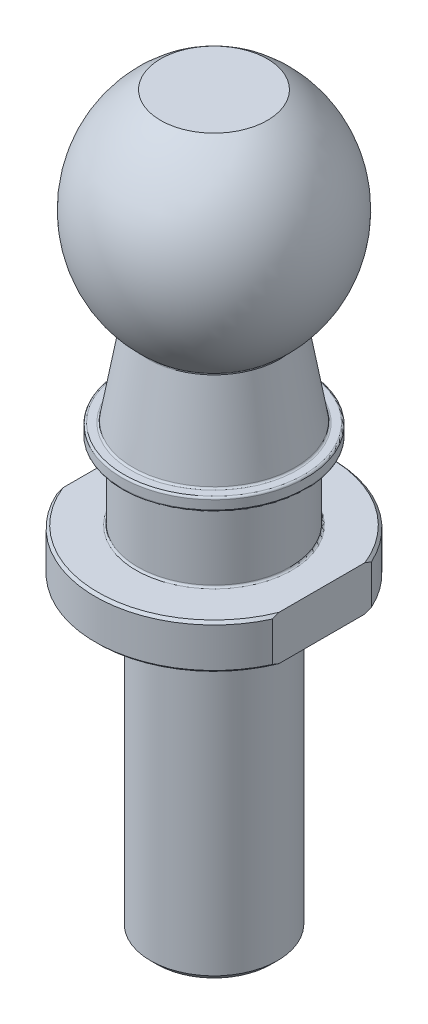
SolidWorks part; units mm, degrees
ref_plane "Plano frontal" through (0, 0, 0) normal (0, 0, 1) x (1, 0, 0)
ref_plane "Plano superior" through (0, 0, 0) normal (0, 1, 0) x (1, 0, 0)
ref_plane "Plano direito" through (0, 0, 0) normal (1, 0, 0) x (0, 0, -1)
sketch "Esboço1" plane through (0, 0, 0) normal (0, 0, 1) x (1, 0, 0)
  line L0 (0, 52.4807) -> (0, -52.9589) construction
  line L1 (0, -52.9589) -> (5, -52.9589)
  line L2 (5, -52.9589) -> (5, -28.7589)
  line L3 (5, -28.7589) -> (9.35, -28.7589)
  line L4 (9.35, -28.7589) -> (9.35, -25.2589)
  line L5 (9.35, -25.2589) -> (6, -25.2589)
  line L6 (6, -25.2589) -> (6, -19.2589)
  line L7 (6, -19.2589) -> (7.25, -19.2589)
  line L8 (7.25, -19.2589) -> (7.25, -18.2589)
  line L9 (7.25, -18.2589) -> (6.4, -18.2589)
  line L10 (6.4, -18.2589) -> (5.175, -11.2589)
  line L11 (4.2023, 4.4411) -> (0, 4.4411)
  line L12 (0, 4.4411) -> (0, -52.9589)
  arc A0 (5.175, -11.2589) -> (4.2023, 4.4411) centre (-0.9606, -3.7589) ccw
  dimension "D7" = 9.69
  dimension "D1" = 5
  dimension "D2" = 9.35
  dimension "D3" = 6
  dimension "D4" = 7.25
  dimension "D5" = 6.4
  dimension "D6" = 5.175
  dimension "D8" = 24.2
  dimension "D9" = 3.5
  dimension "D10" = 6
  dimension "D11" = 1
  dimension "D12" = 7
  dimension "D13" = 25
  dimension "D14" = 57.4
revolve "Revolução1" add sketch "Esboço1" angle 360 about L0
fillet "Filete3" radius 0.15 5 edges at (0, -18.2589, 7.25) (0, -19.2589, 7.25) (0, -19.2589, 6) (0, -18.2589, 6.4) (0, -11.2589, 5.175)
chamfer "Chanfro1" distance 0.2 angle 45 2 edges at (0, -28.7589, 9.35) (0, -25.2589, 9.35)
fillet "Filete4" radius 0.15 1 edges at (0, -25.2589, 6)
chamfer "Chanfro2" distance 0.5 angle 45 1 edges at (0, -52.9589, 5)
sketch "Esboço2" plane through (0, -25.2589, 0) normal (0, 1, 0) x (1, 0, 0)
  line L0 (11.6973, -13.7348) -> (8.5, -13.7348)
  line L1 (-8.5, -13.7348) -> (-8.5, 10.9528)
  line L2 (-8.5, 10.9528) -> (-11.6973, 10.9528)
  line L3 (-11.6973, 10.9528) -> (-11.6973, -13.7348)
  line L4 (-11.6973, -13.7348) -> (-8.5, -13.7348)
  line L5 (0, 0) -> (0, -16.0721) construction
  line L6 (11.6973, 10.9528) -> (11.6973, -13.7348)
  line L7 (8.5, 10.9528) -> (11.6973, 10.9528)
  line L8 (8.5, -13.7348) -> (8.5, 10.9528)
extrude "Corte-extrusão1" cut sketch "Esboço2" against normal through all
sketch "Esboço3" plane through (0, -52.9589, 0) normal (0, -1, 0) x (1, 0, 0)
  line L1 (2.8868, 0) -> (1.4434, 2.5)
  line L2 (1.4434, 2.5) -> (-1.4434, 2.5)
  line L3 (-1.4434, 2.5) -> (-2.8868, 0)
  line L4 (-2.8868, 0) -> (-1.4434, -2.5)
  line L5 (-1.4434, -2.5) -> (1.4434, -2.5)
  line L6 (1.4434, -2.5) -> (2.8868, 0)
  circle A0 centre (0, 0) radius 2.5 construction
  dimension "D1" = 5
extrude "Corte-extrusão2" cut sketch "Esboço3" against normal blind 5
